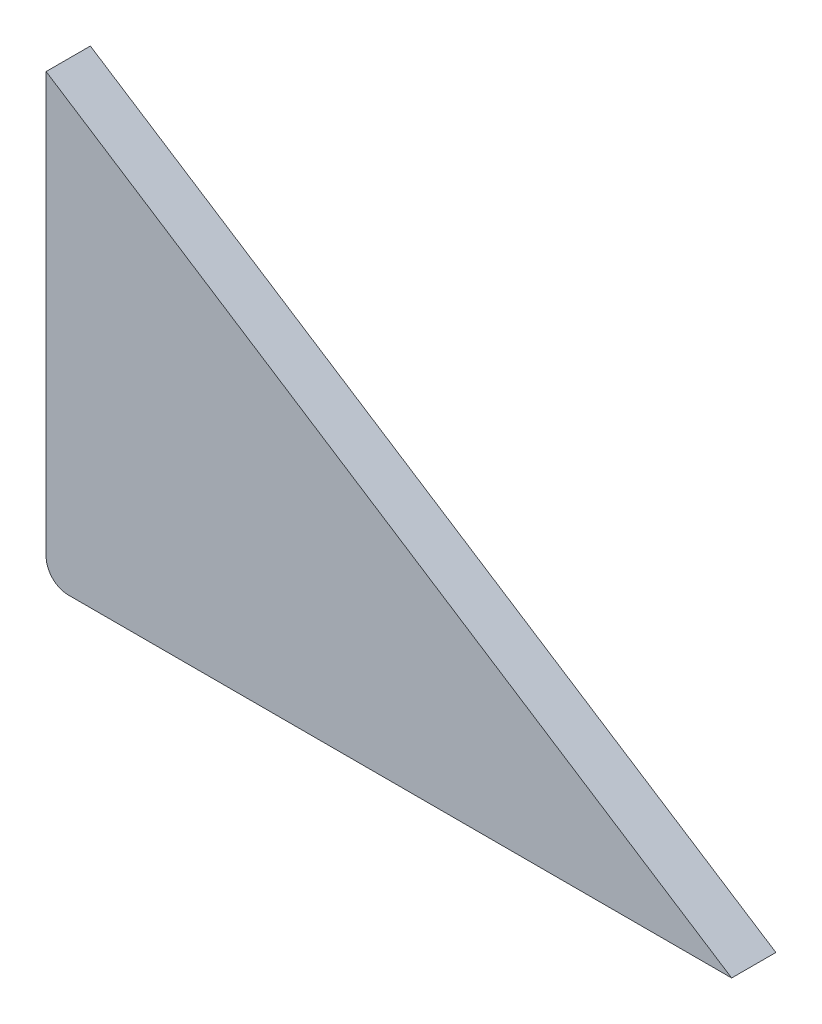
SolidWorks part; units mm, degrees
material "Hexcel AS4C (3000 Filaments)"
ref_plane "Front Plane" through (0, 0, 0) normal (0, 0, 1) x (1, 0, 0)
ref_plane "Top Plane" through (0, 0, 0) normal (0, 1, 0) x (1, 0, 0)
ref_plane "Right Plane" through (0, 0, 0) normal (1, 0, 0) x (0, 0, -1)
sketch "Sketch2" plane through (0, 0, 0) normal (0, 0, 1) x (1, 0, 0)
  line L0 (0, 0) -> (98.425, 0)
  line L1 (98.425, 0) -> (0, 63.5)
  line L2 (0, 63.5) -> (0, 0)
  dimension "D1" = 98.425
  dimension "D2" = 63.5
extrude "Boss-Extrude1" add sketch "Sketch2" along normal blind 6.35
fillet "Fillet1" radius 3.175 1 edges at (0, 0, 3.175)
